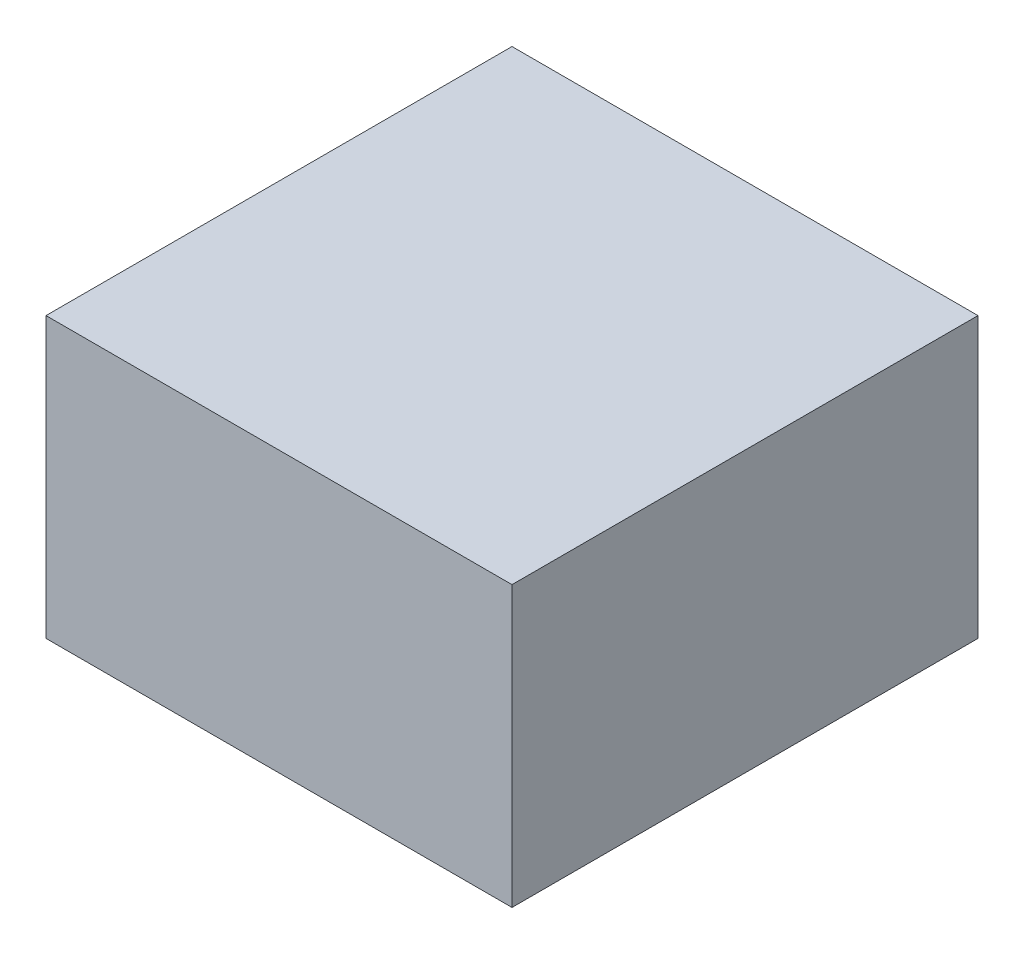
SolidWorks part; units mm, degrees
material "Cast Alloy Steel"
ref_plane "Front Plane" through (0, 0, 0) normal (0, 0, 1) x (1, 0, 0)
ref_plane "Top Plane" through (0, 0, 0) normal (0, 1, 0) x (1, 0, 0)
ref_plane "Right Plane" through (0, 0, 0) normal (1, 0, 0) x (0, 0, -1)
sketch "Sketch1" plane through (0, 0, 0) normal (0, 1, 0) x (1, 0, 0)
  line L1 (0, 0) -> (5, 0)
  line L2 (0, 0) -> (0, -5)
  line L3 (0, -5) -> (5, -5)
  line L4 (5, 0) -> (5, -5)
  dimension "D1" = 5
  dimension "D2" = 5
extrude "Boss-Extrude1" add sketch "Sketch1" along normal blind 3
